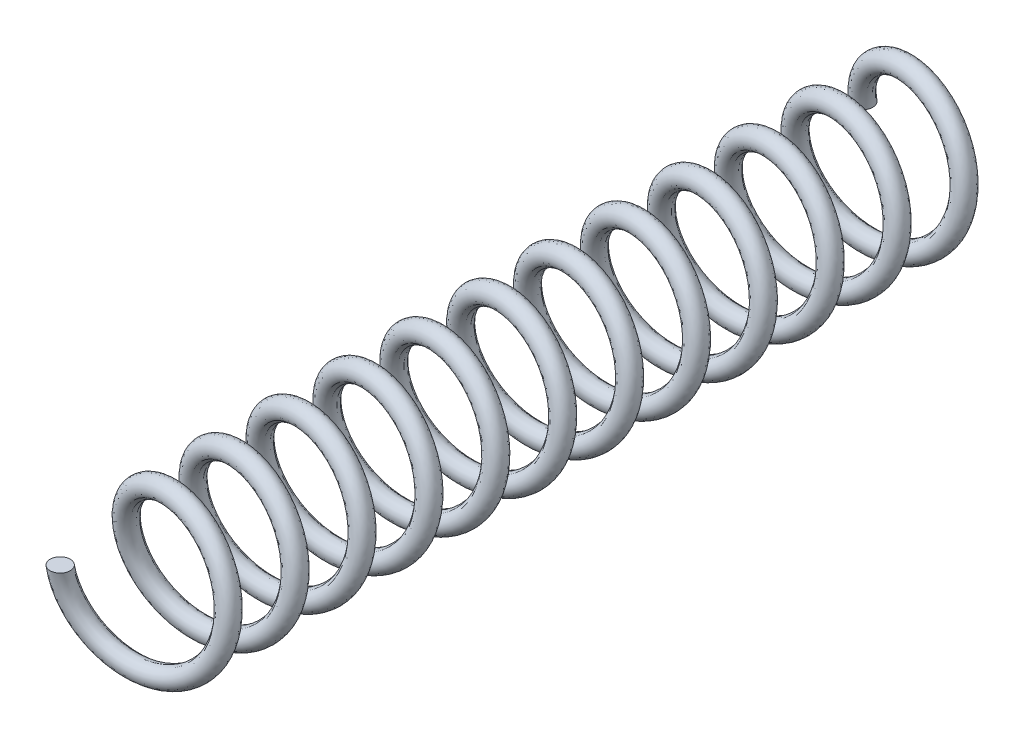
SolidWorks part; units mm, degrees
ref_plane "Front Plane" through (0, 0, 0) normal (0, 0, 1) x (1, 0, 0)
ref_plane "Top Plane" through (0, 0, 0) normal (0, 1, 0) x (1, 0, 0)
ref_plane "Right Plane" through (0, 0, 0) normal (1, 0, 0) x (0, 0, -1)
sketch "Sketch1" plane through (0, 0, 0) normal (0, 0, 1) x (1, 0, 0)
  circle A0 centre (0, 0) radius 5
  dimension "D1" = 10
curve "Helix/Spiral1" pitch 5 height 60 turns 12
sketch "Sketch2" plane through (0, 0, 0) normal (0, 1, 0) x (1, 0, 0)
  circle A0 centre (-5, 0) radius 0.75
  spline S0 degree 3 poles (-5, 0) (-5, -0.1035) (-4.7397, -0.3128) (-3.6276, -0.6249) (-1.9632, -0.9375) (0, -1.25) (1.9632, -1.5625) (3.6276, -1.875) (4.7397, -2.1875) (5.1302, -2.5) (4.7397, -2.8125) (3.6276, -3.125) (1.9632, -3.4375) (0, -3.75) (-1.9632, -4.0625) (-3.6276, -4.375) (-4.7397, -4.6875) (-5.1302, -5) (-4.7397, -5.3125) (-3.6276, -5.625) (-1.9632, -5.9375) (0, -6.25) (1.9632, -6.5625) (3.6276, -6.875) (4.7397, -7.1875) (5.1302, -7.5) (4.7397, -7.8125) (3.6276, -8.125) (1.9632, -8.4375) (0, -8.75) (-1.9632, -9.0625) (-3.6276, -9.375) (-4.7397, -9.6875) (-5.1302, -10) (-4.7397, -10.3125) (-3.6276, -10.625) (-1.9632, -10.9375) (0, -11.25) (1.9632, -11.5625) (3.6276, -11.875) (4.7397, -12.1875) (5.1302, -12.5) (4.7397, -12.8125) (3.6276, -13.125) (1.9632, -13.4375) (0, -13.75) (-1.9632, -14.0625) (-3.6276, -14.375) (-4.7397, -14.6875) (-5.1302, -15) (-4.7397, -15.3125) (-3.6276, -15.625) (-1.9632, -15.9375) (0, -16.25) (1.9632, -16.5625) (3.6276, -16.875) (4.7397, -17.1875) (5.1302, -17.5) (4.7397, -17.8125) (3.6276, -18.125) (1.9632, -18.4375) (0, -18.75) (-1.9632, -19.0625) (-3.6276, -19.375) (-4.7397, -19.6875) (-5.1302, -20) (-4.7397, -20.3125) (-3.6276, -20.625) (-1.9632, -20.9375) (0, -21.25) (1.9632, -21.5625) (3.6276, -21.875) (4.7397, -22.1875) (5.1302, -22.5) (4.7397, -22.8125) (3.6276, -23.125) (1.9632, -23.4375) (0, -23.75) (-1.9632, -24.0625) (-3.6276, -24.375) (-4.7397, -24.6875) (-5.1302, -25) (-4.7397, -25.3125) (-3.6276, -25.625) (-1.9632, -25.9375) (0, -26.25) (1.9632, -26.5625) (3.6276, -26.875) (4.7397, -27.1875) (5.1302, -27.5) (4.7397, -27.8125) (3.6276, -28.125) (1.9632, -28.4375) (0, -28.75) (-1.9632, -29.0625) (-3.6276, -29.375) (-4.7397, -29.6875) (-5.1302, -30) (-4.7397, -30.3125) (-3.6276, -30.625) (-1.9632, -30.9375) (0, -31.25) (1.9632, -31.5625) (3.6276, -31.875) (4.7397, -32.1875) (5.1302, -32.5) (4.7397, -32.8125) (3.6276, -33.125) (1.9632, -33.4375) (0, -33.75) (-1.9632, -34.0625) (-3.6276, -34.375) (-4.7397, -34.6875) (-5.1302, -35) (-4.7397, -35.3125) (-3.6276, -35.625) (-1.9632, -35.9375) (0, -36.25) (1.9632, -36.5625) (3.6276, -36.875) (4.7397, -37.1875) (5.1302, -37.5) (4.7397, -37.8125) (3.6276, -38.125) (1.9632, -38.4375) (0, -38.75) (-1.9632, -39.0625) (-3.6276, -39.375) (-4.7397, -39.6875) (-5.1302, -40) (-4.7397, -40.3125) (-3.6276, -40.625) (-1.9632, -40.9375) (0, -41.25) (1.9632, -41.5625) (3.6276, -41.875) (4.7397, -42.1875) (5.1302, -42.5) (4.7397, -42.8125) (3.6276, -43.125) (1.9632, -43.4375) (0, -43.75) (-1.9632, -44.0625) (-3.6276, -44.375) (-4.7397, -44.6875) (-5.1302, -45) (-4.7397, -45.3125) (-3.6276, -45.625) (-1.9632, -45.9375) (0, -46.25) (1.9632, -46.5625) (3.6276, -46.875) (4.7397, -47.1875) (5.1302, -47.5) (4.7397, -47.8125) (3.6276, -48.125) (1.9632, -48.4375) (0, -48.75) (-1.9632, -49.0625) (-3.6276, -49.375) (-4.7397, -49.6875) (-5.1302, -50) (-4.7397, -50.3125) (-3.6276, -50.625) (-1.9632, -50.9375) (0, -51.25) (1.9632, -51.5625) (3.6276, -51.875) (4.7397, -52.1875) (5.1302, -52.5) (4.7397, -52.8125) (3.6276, -53.125) (1.9632, -53.4375) (0, -53.75) (-1.9632, -54.0625) (-3.6276, -54.375) (-4.7397, -54.6875) (-5.1302, -55) (-4.7397, -55.3125) (-3.6276, -55.625) (-1.9632, -55.9375) (0, -56.25) (1.9632, -56.5625) (3.6276, -56.875) (4.7397, -57.1875) (5.1302, -57.5) (4.7397, -57.8125) (3.6276, -58.125) (1.9632, -58.4375) (0, -58.75) (-1.9632, -59.0625) (-3.6276, -59.3751) (-4.7397, -59.6872) (-5, -59.8965) (-5, -60) knots 0 0 0 0 0.005208 0.010417 0.015625 0.020833 0.026042 0.03125 0.036458 0.041667 0.046875 0.052083 0.057292 0.0625 0.067708 0.072917 0.078125 0.083333 0.088542 0.09375 0.098958 0.104167 0.109375 0.114583 0.119792 0.125 0.130208 0.135417 0.140625 0.145833 0.151042 0.15625 0.161458 0.166667 0.171875 0.177083 0.182292 0.1875 0.192708 0.197917 0.203125 0.208333 0.213542 0.21875 0.223958 0.229167 0.234375 0.239583 0.244792 0.25 0.255208 0.260417 0.265625 0.270833 0.276042 0.28125 0.286458 0.291667 0.296875 0.302083 0.307292 0.3125 0.317708 0.322917 0.328125 0.333333 0.338542 0.34375 0.348958 0.354167 0.359375 0.364583 0.369792 0.375 0.380208 0.385417 0.390625 0.395833 0.401042 0.40625 0.411458 0.416667 0.421875 0.427083 0.432292 0.4375 0.442708 0.447917 0.453125 0.458333 0.463542 0.46875 0.473958 0.479167 0.484375 0.489583 0.494792 0.5 0.505208 0.510417 0.515625 0.520833 0.526042 0.53125 0.536458 0.541667 0.546875 0.552083 0.557292 0.5625 0.567708 0.572917 0.578125 0.583333 0.588542 0.59375 0.598958 0.604167 0.609375 0.614583 0.619792 0.625 0.630208 0.635417 0.640625 0.645833 0.651042 0.65625 0.661458 0.666667 0.671875 0.677083 0.682292 0.6875 0.692708 0.697917 0.703125 0.708333 0.713542 0.71875 0.723958 0.729167 0.734375 0.739583 0.744792 0.75 0.755208 0.760417 0.765625 0.770833 0.776042 0.78125 0.786458 0.791667 0.796875 0.802083 0.807292 0.8125 0.817708 0.822917 0.828125 0.833333 0.838542 0.84375 0.848958 0.854167 0.859375 0.864583 0.869792 0.875 0.880208 0.885417 0.890625 0.895833 0.901042 0.90625 0.911458 0.916667 0.921875 0.927083 0.932292 0.9375 0.942708 0.947917 0.953125 0.958333 0.963542 0.96875 0.973958 0.979167 0.984375 0.989583 0.994792 1 1 1 1 construction
  dimension "D1" = 1.5
sweep "Sweep1" add profiles "Sketch2" path "Helix/Spiral1"
